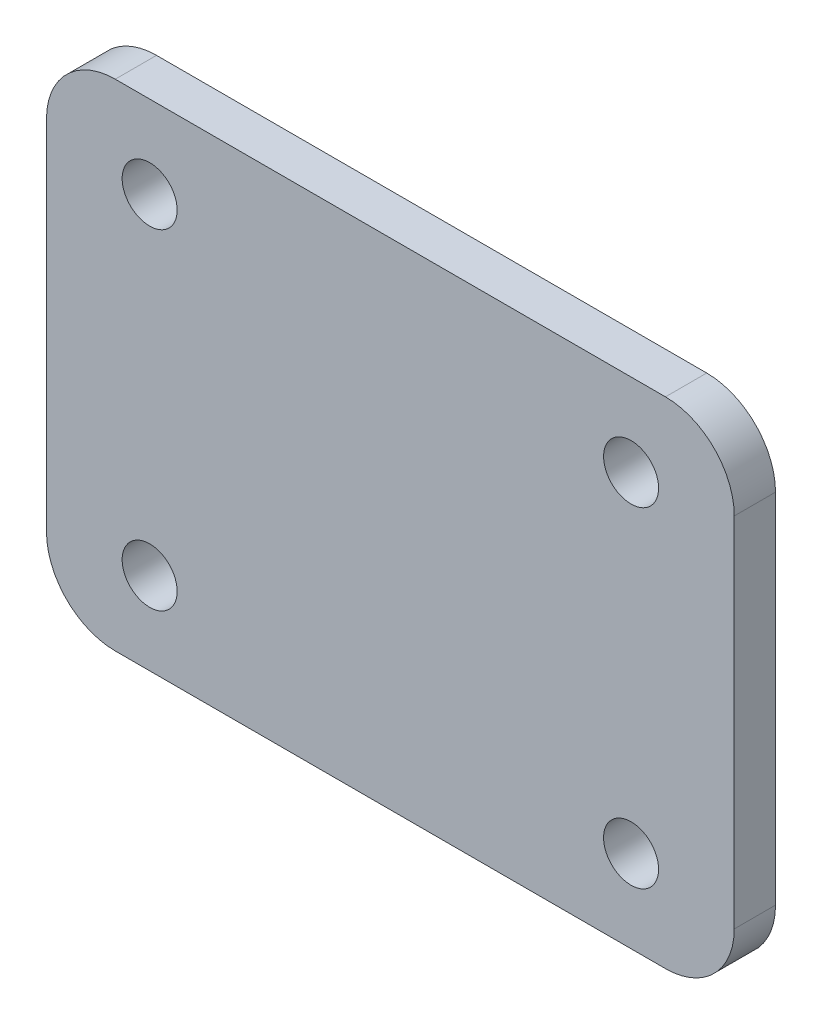
SolidWorks part; units mm, degrees
ref_plane "前视基准面" through (0, 0, 0) normal (0, 0, 1) x (1, 0, 0)
ref_plane "上视基准面" through (0, 0, 0) normal (0, 1, 0) x (1, 0, 0)
ref_plane "右视基准面" through (0, 0, 0) normal (1, 0, 0) x (0, 0, -1)
other "Configuration Table"
sketch "草图1" plane through (0, 0, 0) normal (0, 0, 1) x (1, 0, 0)
  line L0 (25, 18) -> (-25, 18)
  line L1 (-25, 18) -> (-25, -18)
  line L2 (-25, -18) -> (25, -18)
  line L3 (25, -18) -> (25, 18)
  circle A0 centre (17.5, -12) radius 2
  circle A1 centre (-17.5, -12) radius 2
  circle A2 centre (17.5, 12) radius 2
  circle A3 centre (-17.5, 12) radius 2
extrude "凸台-拉伸1" add sketch "草图1" along normal blind 3
fillet "圆角1" radius 5 4 edges at (25, -18, 1.5) (-25, -18, 1.5) (-25, 18, 1.5) (25, 18, 1.5)
